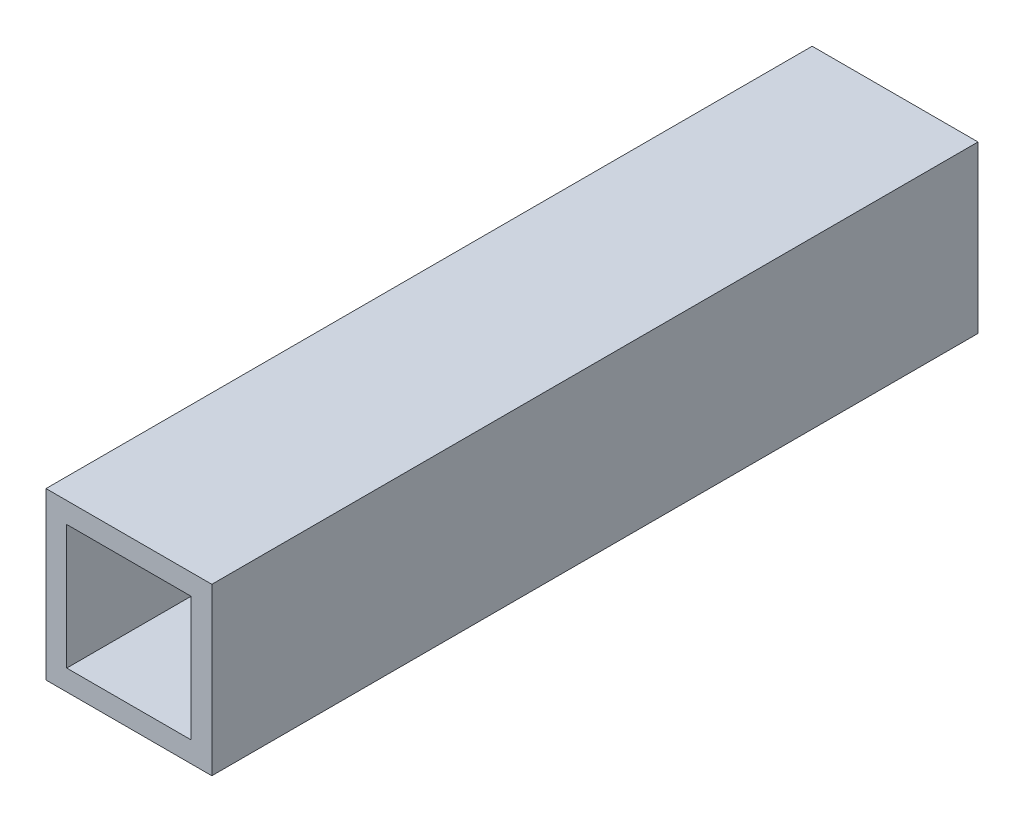
SolidWorks part; units mm, degrees
ref_plane "Front Plane" through (0, 0, 0) normal (0, 0, 1) x (1, 0, 0)
ref_plane "Top Plane" through (0, 0, 0) normal (0, 1, 0) x (1, 0, 0)
ref_plane "Right Plane" through (0, 0, 0) normal (1, 0, 0) x (0, 0, -1)
sketch "Sketch1" plane through (0, 0, 0) normal (0, 0, 1) x (1, 0, 0)
  line L0 (12.7, 0) -> (9.525, 0) construction
  line L1 (-12.7, 0) -> (12.7, 0) construction
  line L2 (0, 12.7) -> (0, -12.7)
  point P7 (0, 0)
sketch "Sketch2" plane through (0, 0, 0) normal (1, 0, 0) x (0, 0, -1)
  line L0 (58.674, 0) -> (-58.674, 0)
  point P4 (0, 0)
  dimension "Length" = 117.348
sketch "Sketch3" plane through (0, 0, 0) normal (0, 0, 1) x (1, 0, 0)
  line L0 (-12.7, 0) -> (12.7, 0) construction
  line L5 (12.7, -12.7) -> (-12.7, -12.7)
  line L6 (12.7, -12.7) -> (12.7, 12.7)
  line L11 (12.7, 12.7) -> (-12.7, 12.7)
  line L12 (-12.7, -12.7) -> (-12.7, 12.7)
  line L14 (12.7, -12.7) -> (-12.7, 12.7) construction
  line L15 (12.7, 12.7) -> (-12.7, -12.7) construction
  line L16 (9.525, -9.525) -> (-9.525, -9.525)
  line L17 (9.525, -9.525) -> (9.525, 9.525)
  line L18 (9.525, 9.525) -> (-9.525, 9.525)
  line L19 (-9.525, -9.525) -> (-9.525, 9.525)
  line L20 (9.525, -9.525) -> (-9.525, 9.525) construction
  line L21 (9.525, 9.525) -> (-9.525, -9.525) construction
  point P0 (0, 0)
  point P5 (0, 0)
  point P13 (9.525, -12.7)
  dimension "D1" = 3.175
  dimension "D3" = 25.4
  dimension "D4" = 25.4
extrude "Boss-Extrude1" add sketch "Sketch3" along normal up to vertex (58.674 mm away) and the other way up to vertex (58.674 mm away) up to point (0, 0, 58.674) other way up to point (0, 0, -58.674)
sketch "Sketch5" plane through (0, 0, 0) normal (1, 0, 0) x (0, 0, -1)
  line L0 (-58.674, 0) -> (58.674, 0) construction
  line L3 (-58.674, -12.7) -> (-58.674, 12.7) construction
  line L4 (58.674, -12.7) -> (58.674, 12.7) construction
  point P6 (-30.099, 0)
  point P7 (-20.574, 0)
  point P8 (20.574, 0)
  point P10 (30.099, 0)
  dimension "D1" = 28.575
  dimension "D2" = 38.1
  dimension "D3" = 28.575
  dimension "D4" = 38.1
equation "\"D1@Sketch3\"=\"Wall thickness@Sketch1\""
equation "\"D1@Sketch5\"=\"Width@Sketch1\"*1.125"
equation "\"D2@Sketch5\"=\"Width@Sketch1\"*1.5"
equation "\"D3@Sketch5\"=\"D1@Sketch5\""
equation "\"D4@Sketch5\"=\"D2@Sketch5\""
equation "\"D2@Sketch3\"=\"Wall Thickness@Sketch1\""
